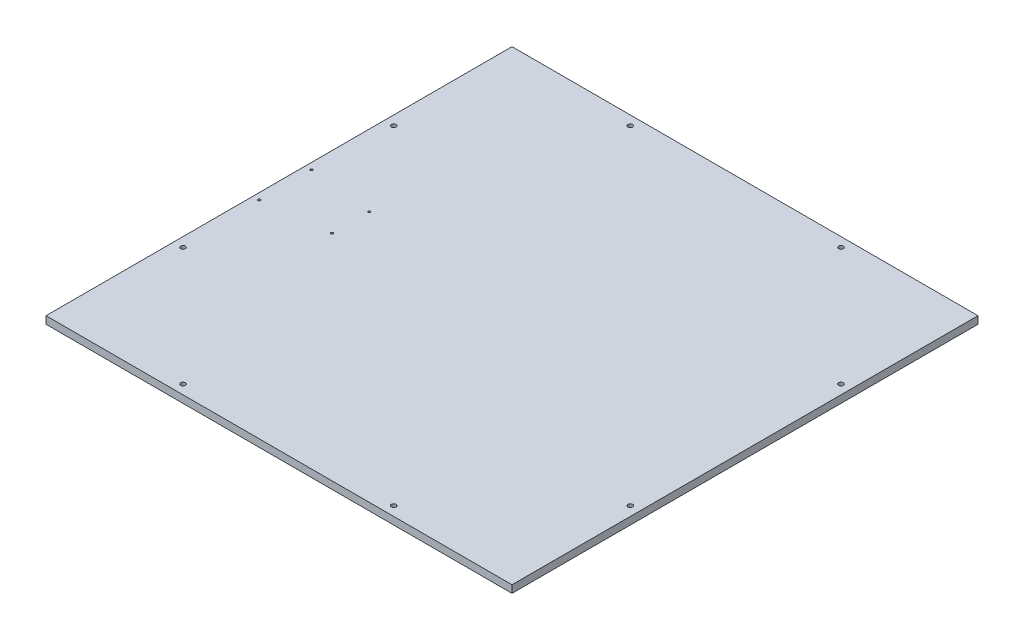
SolidWorks part; units mm, degrees
material "Oak"
ref_plane "Front Plane" through (0, 0, 0) normal (0, 0, 1) x (1, 0, 0)
ref_plane "Top Plane" through (0, 0, 0) normal (0, 1, 0) x (1, 0, 0)
ref_plane "Right Plane" through (0, 0, 0) normal (1, 0, 0) x (0, 0, -1)
sketch "Sketch1" plane through (0, 0, 0) normal (0, 1, 0) x (1, 0, 0)
  line L1 (-250, 250) -> (250, 250)
  line L2 (-250, 250) -> (-250, -250)
  line L3 (-250, -250) -> (250, -250)
  line L4 (250, 250) -> (250, -250)
  line L5 (-250, 250) -> (250, -250) construction
  line L6 (-250, -250) -> (250, 250) construction
  point P0 (0, 0)
  dimension "D1" = 500
  dimension "D2" = 500
extrude "Boss-Extrude1" add sketch "Sketch1" along normal blind 8
sketch "Sketch5" plane through (0, 8, 0) normal (0, 1, 0) x (1, 0, 0)
  line L0 (-4.0803, 0) -> (-250, 0) construction
  line L1 (-250, 250) -> (-250, -250) construction
  circle A0 centre (-243.1518, 28) radius 1.25
  circle A1 centre (-173.1518, 20) radius 1.25
  circle A2 centre (-173.1518, -20) radius 1.25
  circle A3 centre (-243.1518, -28) radius 1.25
sketch "Sketch6" plane through (0, 8, 0) normal (0, 1, 0) x (1, 0, 0)
  line L0 (0, 0) -> (-250, 0) construction
  line L1 (-250, 250) -> (-250, -250) construction
  line L2 (0, 0) -> (0, 250) construction
  line L3 (250, 250) -> (-250, 250) construction
  line L4 (0, 0) -> (-250, 250) construction
  line L5 (-250, -250) -> (250, -250) construction
  line L6 (0, 0) -> (250, 250) construction
  circle A0 centre (-240, -113) radius 2.5
  circle A1 centre (-240, 113) radius 2.5
  circle A2 centre (-113, 240) radius 2.5
  circle A3 centre (113, 240) radius 2.5
  circle A4 centre (240, 113) radius 2.5
  circle A5 centre (240, -113) radius 2.5
  circle A6 centre (113, -240) radius 2.5
  circle A7 centre (-113, -240) radius 2.5
  dimension "D1" = 5
  dimension "D2" = 10
  dimension "D3" = 137
extrude "Cut-Extrude5" cut sketch "Sketch6" against normal up to surface (8 mm away) up to face at (0, 0, 0)
extrude "Cut-Extrude4" cut sketch "Sketch5" against normal up to surface (8 mm away) up to face at (-113, 0, 242.5)
